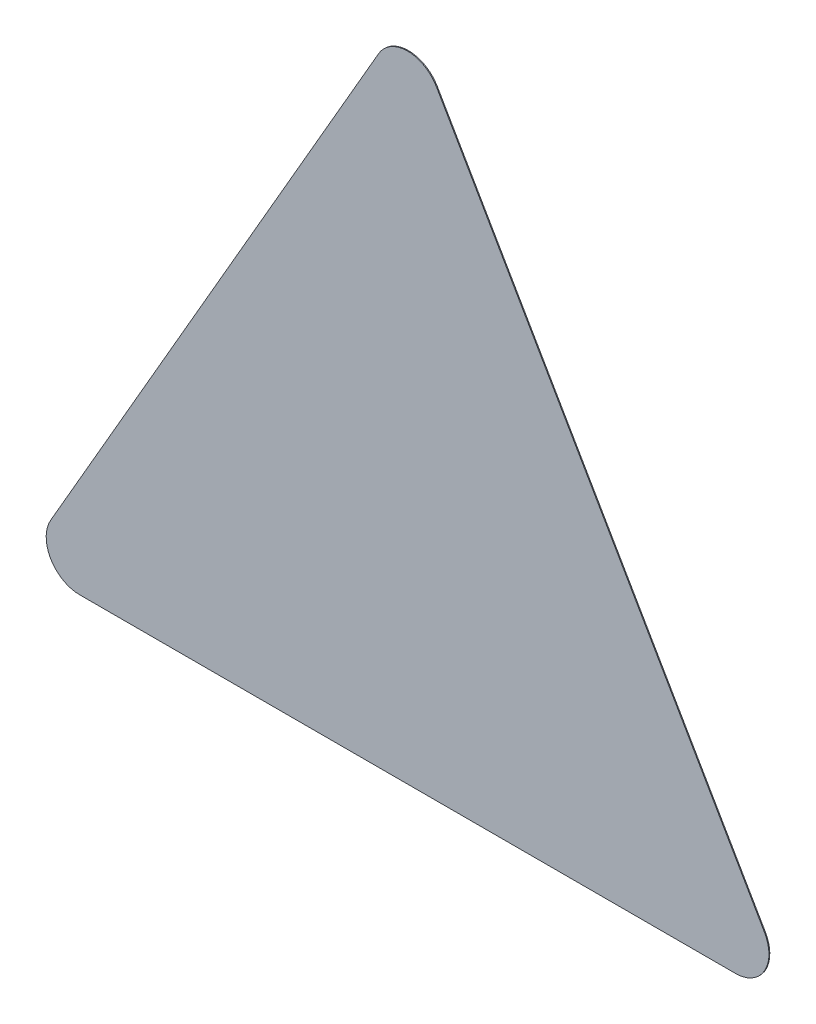
SolidWorks part; units mm, degrees
ref_plane "Front Plane" through (0, 0, 0) normal (0, 0, 1) x (1, 0, 0)
ref_plane "Top Plane" through (0, 0, 0) normal (0, 1, 0) x (1, 0, 0)
ref_plane "Right Plane" through (0, 0, 0) normal (1, 0, 0) x (0, 0, -1)
sketch "Sketch1" plane through (0, 0, 0) normal (0, 0, 1) x (1, 0, 0)
  line L1 (-24.5374, -25) -> (-5, -25)
  line L5 (-26.7024, -21.25) -> (-2.1651, 21.25)
  line L6 (2.1651, 21.25) -> (26.7024, -21.25)
  line L9 (5, -25) -> (24.5374, -25)
  line L14 (0, 25) -> (0, -25) construction
  line L25 (-5, -25) -> (5, -25)
  arc A0 (26.7024, -21.25) -> (24.5374, -25) centre (24.5374, -22.5) cw
  arc A1 (-24.5374, -25) -> (-26.7024, -21.25) centre (-24.5374, -22.5) cw
  arc A2 (2.1651, 21.25) -> (-2.1651, 21.25) centre (0, 20) ccw
  point P0 (0, 0)
  point P1 (0, 0)
  point P3 (0, 0)
  point P5 (0, 0)
  point P9 (28.8675, -25)
  point P12 (-28.8675, -25)
  dimension "D3" = 25
  dimension "D6" = 2.5
  dimension "D1" = 50
  dimension "D2" = 25
  dimension "D4" = 25
  dimension "D5" = 28.8675
  dimension "D20" = 28.8675
extrude "Boss-Extrude1" add sketch "Sketch1" along normal blind 0.065
